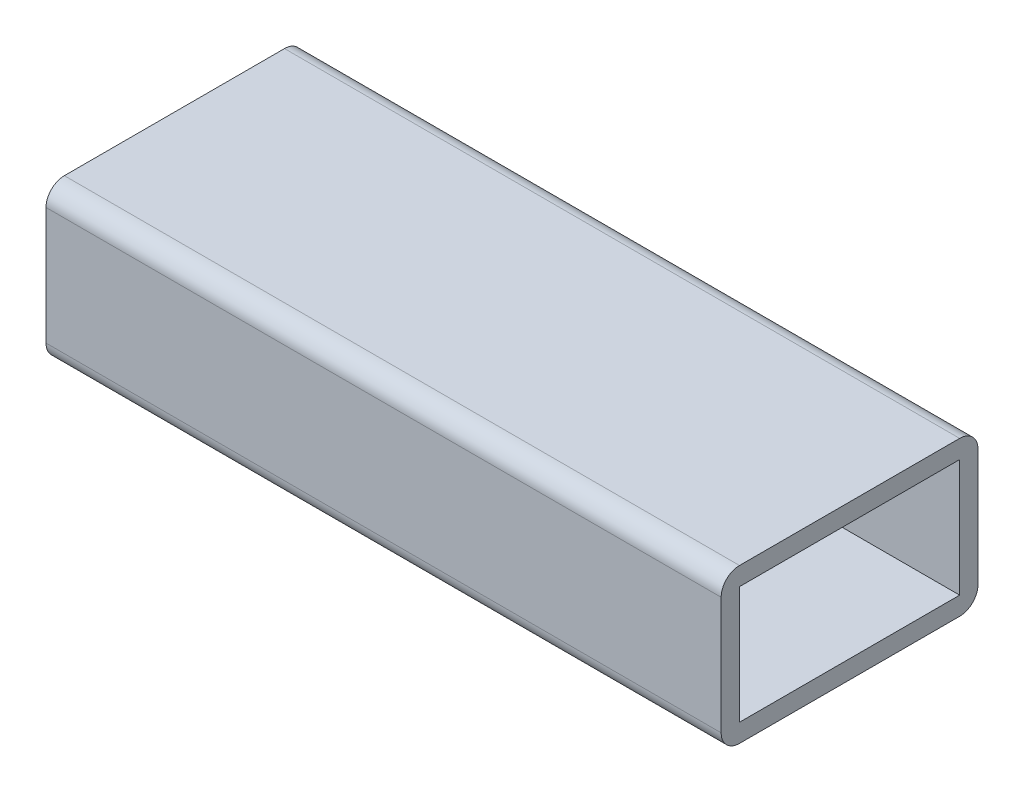
SolidWorks part; units mm, degrees
ref_plane "前视基准面" through (0, 0, 0) normal (0, 0, 1) x (1, 0, 0)
ref_plane "上视基准面" through (0, 0, 0) normal (0, 1, 0) x (1, 0, 0)
ref_plane "右视基准面" through (0, 0, 0) normal (1, 0, 0) x (0, 0, -1)
sketch "草图1" plane through (0, 0, 0) normal (1, 0, 0) x (0, 0, -1)
  line L0 (-1.75, -1.05) -> (-1.75, 1.05)
  line L1 (-1.5, -0.8) -> (1.5, -0.8)
  line L2 (-1.5, -0.8) -> (-1.5, 0.8)
  line L3 (-1.5, 0.8) -> (1.5, 0.8)
  line L4 (1.5, -0.8) -> (1.5, 0.8)
  line L5 (-1.5, -0.8) -> (1.5, 0.8) construction
  line L6 (-1.5, 0.8) -> (1.5, -0.8) construction
  line L7 (-1.75, 1.05) -> (1.75, 1.05)
  line L8 (1.75, -1.05) -> (1.75, 1.05)
  line L9 (-1.75, -1.05) -> (1.75, -1.05)
  point P0 (0, 0)
  dimension "D1" = 3
  dimension "D2" = 1.6
  dimension "D3" = 0.25
extrude "凸台-拉伸1" add sketch "草图1" along normal blind 9.2
fillet "圆角1" radius 0.25 4 edges at (4.6, 1.05, -1.75) (4.6, -1.05, -1.75) (4.6, -1.05, 1.75) (4.6, 1.05, 1.75)
